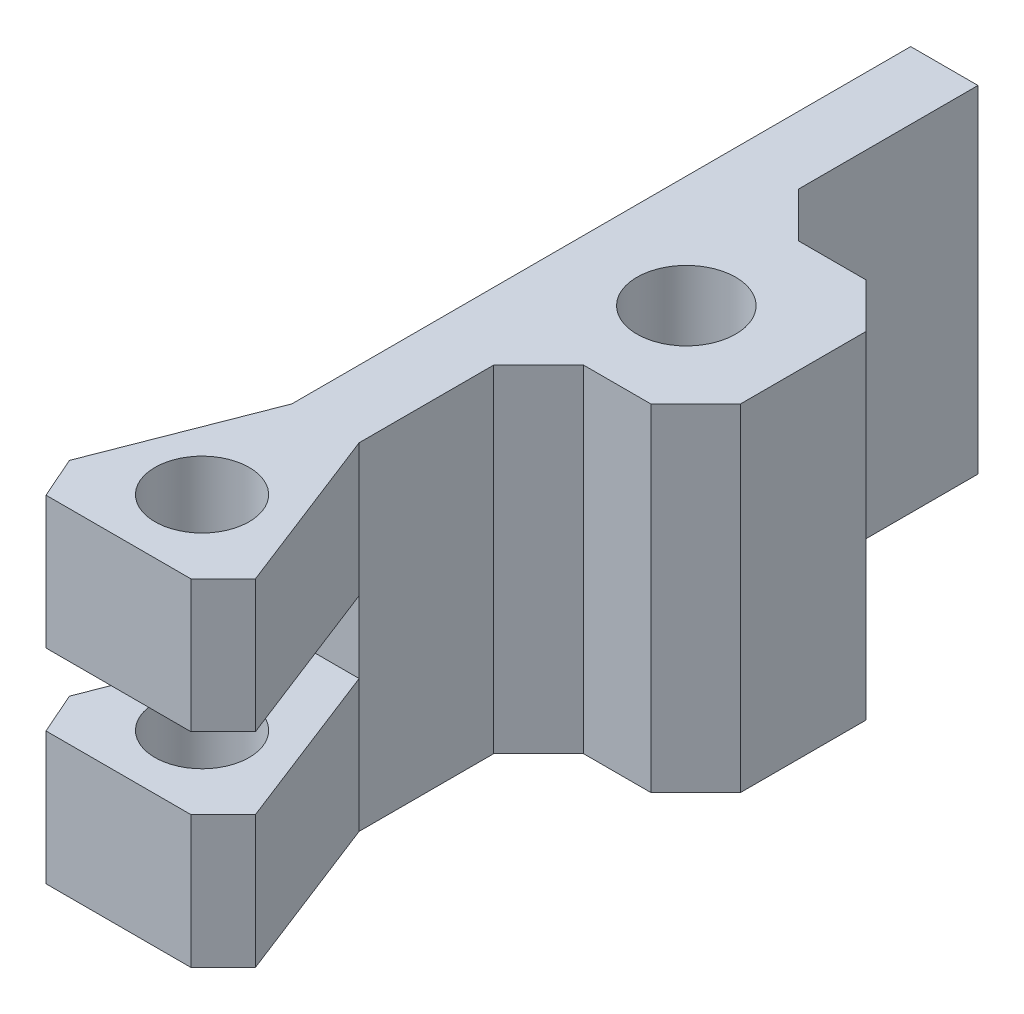
SolidWorks part; units mm, degrees
ref_plane "Front Plane" through (0, 0, 0) normal (0, 0, 1) x (1, 0, 0)
ref_plane "Top Plane" through (0, 0, 0) normal (0, 1, 0) x (1, 0, 0)
ref_plane "Right Plane" through (0, 0, 0) normal (1, 0, 0) x (0, 0, -1)
sketch "Sketch1" plane through (0, 0, 0) normal (0, 1, 0) x (1, 0, 0)
  line L1 (-3.81, 0) -> (-3.81, 46.4599) construction
  line L2 (-3.81, 46.4599) -> (0, 46.4599)
  line L3 (0, 46.4599) -> (0, 33.7599)
  line L6 (8.89, 21.59) -> (0, 21.59)
  line L8 (0, 21.59) -> (0, 0) construction
  line L14 (-3.81, 27.4099) -> (2.54, 27.4099) construction
  line L15 (2.54, 27.4099) -> (0, 21.59) construction
  line L16 (2.54, 27.4099) -> (8.89, 27.4099) construction
  line L17 (8.89, 33.7599) -> (8.89, 21.59)
  line L18 (0, 33.7599) -> (8.89, 33.7599)
  line L19 (2.54, 27.4099) -> (2.54, 33.7599) construction
  line L23 (-3.81, 46.4599) -> (-3.81, 11.43)
  line L27 (0, 21.59) -> (0, 11.43)
  line L28 (0, 11.43) -> (4.445, 0)
  line L29 (4.445, 0) -> (-8.255, 0)
  line L30 (-8.255, 0) -> (-3.81, 11.43)
  line L31 (0, 11.43) -> (-3.81, 11.43) construction
  line L32 (-1.905, 11.43) -> (-1.905, 0)
  circle A0 centre (2.54, 27.4099) radius 2.794
  circle A3 centre (-1.905, 4.445) radius 2.667
  point P16 (-1.905, 4.445)
  point P20 (-5.9718, 0)
  point P23 (4.2872, 0)
  point P24 (0, 8.5521)
  point P25 (-1.905, 3.9235)
  dimension "D4" = 5.588
  dimension "D9" = 5.334
  dimension "D1" = 21.59
  dimension "D2" = 3.81
  dimension "D3" = 3.81
  dimension "D5" = 6.35
  dimension "D6" = 12.7
  dimension "D7" = 2.54
  dimension "D8" = 19.05
  dimension "D10" = 11.43
  dimension "D11" = 12.7
  dimension "D12" = 4.445
extrude "Boss-Extrude1" add sketch "Sketch1" along normal blind 19.05 contours L30 L23 L2 L3 L18 L17 L6 L27 L28 L29 | A3 | A0
chamfer "Chamfer1" distance 2.54 angle 45 4 edges at (8.89, 9.525, -21.59) (8.89, 9.525, -33.7599) (0, 9.525, -33.7599) (0, 9.525, -21.59)
chamfer "Chamfer2" distance 2.54 angle 45 2 edges at (4.445, 9.525, 0) (-8.255, 9.525, 0)
sketch "Sketch2" plane through (0, 0, 0) normal (0, 0, 1) x (1, 0, 0)
  line L0 (-7.3344, 0) -> (-7.3344, 19.05) construction
  line L1 (-7.3344, 11.557) -> (3.7338, 11.557)
  line L2 (-7.3344, 11.557) -> (-7.3344, 7.493)
  line L3 (-7.3344, 7.493) -> (3.7338, 7.493)
  line L4 (3.7338, 11.557) -> (3.7338, 7.493)
  line L5 (3.7338, 19.05) -> (3.7338, 0) construction
  point P8 (-7.3344, 9.525)
  point P9 (-7.3344, 9.525)
  dimension "D1" = 4.064
extrude "notch" cut sketch "Sketch2" against normal blind 11.43
